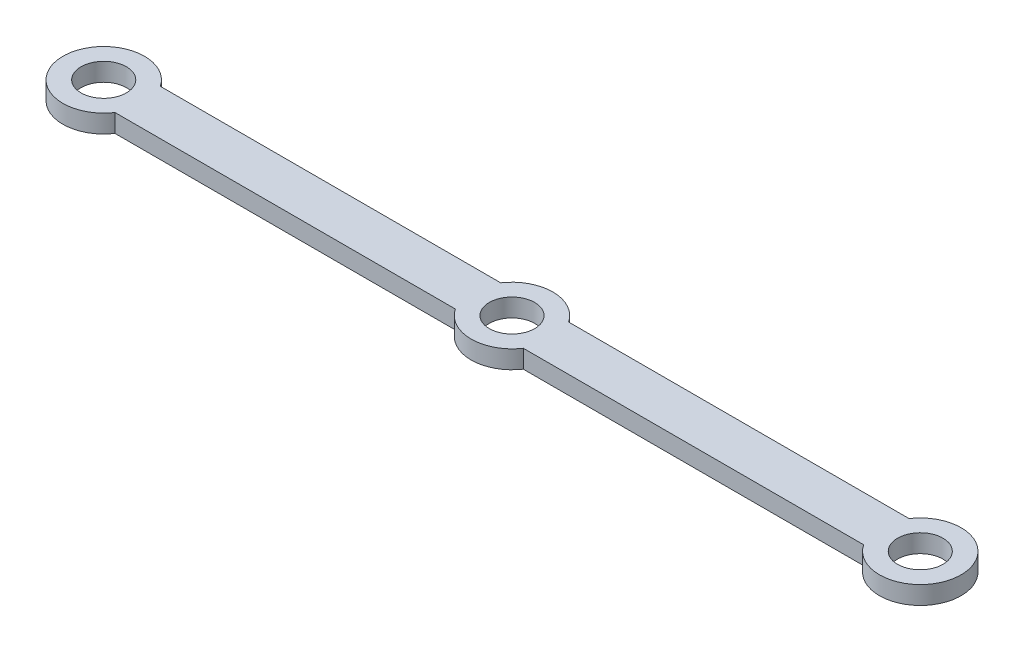
SolidWorks part; units mm, degrees
ref_plane "Front Plane" through (0, 0, 0) normal (0, 0, 1) x (1, 0, 0)
ref_plane "Top Plane" through (0, 0, 0) normal (0, 1, 0) x (1, 0, 0)
ref_plane "Right Plane" through (0, 0, 0) normal (1, 0, 0) x (0, 0, -1)
sketch "Sketch2" plane through (0, 0, 0) normal (0, 1, 0) x (1, 0, 0)
  line L0 (0, 0) -> (90, 0) construction
  line L1 (3.7417, 2.5) -> (86.2583, 2.5)
  line L2 (3.7417, -2.5) -> (86.2583, -2.5)
  circle A0 centre (0, 0) radius 4.5
  circle A1 centre (0, 0) radius 2.5
  circle A2 centre (45, 0) radius 4.5
  circle A3 centre (45, 0) radius 2.5
  circle A4 centre (90, 0) radius 4.5
  circle A5 centre (90, 0) radius 2.5
  dimension "D1" = 9
  dimension "D2" = 5
  dimension "D3" = 90
  dimension "D4" = 45
extrude "Boss-Extrude1" add sketch "Sketch2" along normal blind 2
